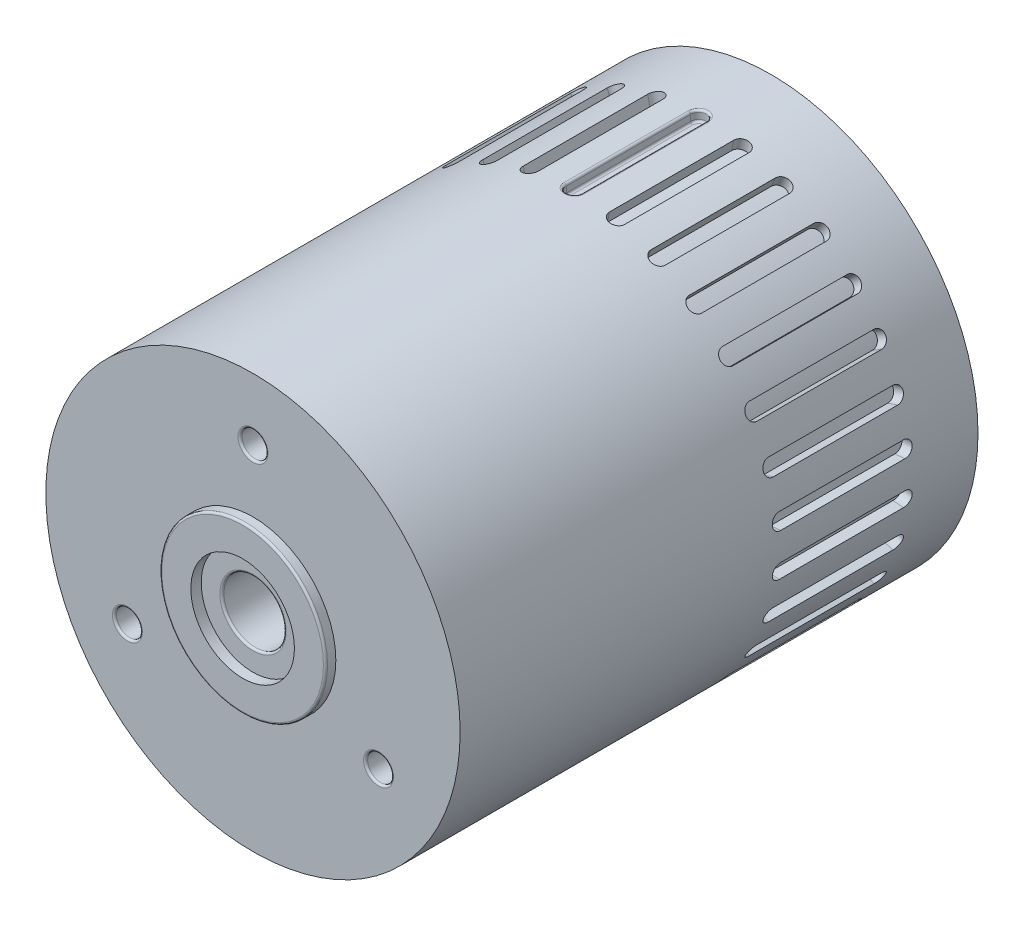
SolidWorks part; units mm, degrees
ref_plane "Front Plane" through (0, 0, 0) normal (0, 0, 1) x (1, 0, 0)
ref_plane "Top Plane" through (0, 0, 0) normal (0, 1, 0) x (1, 0, 0)
ref_plane "Right Plane" through (0, 0, 0) normal (1, 0, 0) x (0, 0, -1)
sketch "Sketch1" plane through (0, 0, 0) normal (0, 0, 1) x (1, 0, 0)
  circle A0 centre (0, 0) radius 10
  circle A1 centre (0, 0) radius 4 construction
  circle A2 centre (0, 0) radius 2.5 construction
  circle A3 centre (0, 0) radius 1.5 construction
  dimension "D1" = 20
  dimension "D2" = 8
  dimension "D3" = 5
  dimension "D4" = 3
extrude "Boss-Extrude1" add sketch "Sketch1" against normal blind 25
sketch "Sketch4" plane through (0, 0, 0) normal (0, 0, 1) x (1, 0, 0)
  circle A0 centre (0, 0) radius 2.5 construction
  circle A1 centre (0, 0) radius 4 construction
  circle A2 centre (0, 0) radius 2.5
  circle A3 centre (0, 0) radius 4
extrude "Boss-Extrude2" add sketch "Sketch4" along normal blind 0.5
sketch "Sketch5" plane through (0, 0, -25) normal (0, 0, -1) x (-1, 0, 0)
  circle A0 centre (0, 0) radius 1.5
  dimension "D1" = 3
extrude "Boss-Extrude3" add sketch "Sketch5" along normal blind 0.5
sketch "Sketch9" plane through (0, 0, 0) normal (0, 1, 0) x (1, 0, 0)
  line L0 (0, 21.5) -> (0, 15.5) construction
  line L1 (0.375, 21.5) -> (0.375, 15.5)
  line L2 (-0.375, 21.5) -> (-0.375, 15.5)
  line L3 (-10, 0) -> (10, 0) construction
  arc A0 (0.375, 21.5) -> (-0.375, 21.5) centre (0, 21.5) ccw
  arc A1 (-0.375, 15.5) -> (0.375, 15.5) centre (0, 15.5) ccw
  point P2 (0, 18.5)
  dimension "D1" = 0.75
  dimension "D2" = 18.5
  dimension "D3" = 6
extrude "Cut-Extrude3" cut sketch "Sketch9" against normal offset from surface (20.5074 mm away) 0.5 from offset 30
fillet "Fillet1" radius 0.1 8 edges at (-0.375, 9.993, -18.5) (0.0433, 9.9999, -15.1275) (0.375, 9.993, -18.5) (-0.0433, 9.9999, -21.8725) (0.375, 9.4926, -18.5) (-0.0433, 9.4999, -15.1275) (-0.375, 9.4926, -18.5) (0.0433, 9.4999, -21.8725)
pattern_circular "CirPattern3" count 30 over 360 about axis through (0, 0, 0) along (0, 0, 1) of "Cut-Extrude3"
sketch "Sketch10" plane through (0, 0, 0) normal (0, 0, 1) x (1, 0, 0)
  circle A0 centre (0, 0) radius 1.5 construction
  circle A3 centre (0, 0) radius 1.5
extrude "Cut-Extrude4" cut sketch "Sketch10" against normal offset from surface (5.75 mm away) 5.75 up to face at (2.5, 0, 0)
sketch "Sketch14" plane through (0, 0, 0) normal (0, 0, 1) x (1, 0, 0)
  circle A0 centre (0, 7) radius 0.625
  circle A1 centre (6.0622, -3.5) radius 0.625
  circle A2 centre (-6.0622, -3.5) radius 0.625
  point P9 (0, 0)
  dimension "D1" = 1.25
  dimension "D2" = 7
  dimension "D3" = 3
extrude "Cut-Extrude5" cut sketch "Sketch14" against normal blind 5
fillet "Fillet2" radius 0.1 6 edges at (1.5, 0, 0) (4, 0, 0.5) (-5.4372, -3.5, 0) (6.6872, -3.5, 0) (0.625, 7, 0) (-1.5, 0, -25.5)
